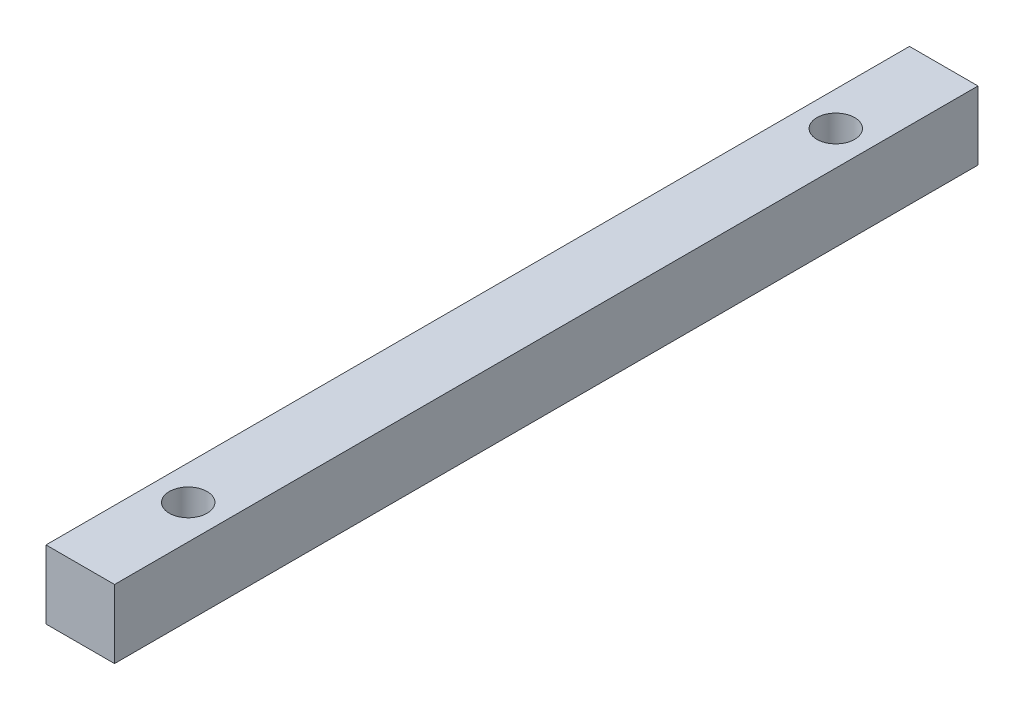
SolidWorks part; units mm, degrees
ref_plane "Front Plane" through (0, 0, 0) normal (0, 0, 1) x (1, 0, 0)
ref_plane "Top Plane" through (0, 0, 0) normal (0, 1, 0) x (1, 0, 0)
ref_plane "Right Plane" through (0, 0, 0) normal (1, 0, 0) x (0, 0, -1)
sketch "Sketch1" plane through (0, 0, 0) normal (0, 0, 1) x (1, 0, 0)
  line L0 (-3.175, 3.175) -> (-3.175, -3.175) construction
  line L1 (-3.175, 3.175) -> (3.175, 3.175) construction
  line L2 (-3.175, 0) -> (0, 0) construction
  line L3 (0, 0) -> (0, 3.175) construction
  dimension "Thickness" = 6.35
  dimension "Width" = 6.35
ref_plane "Plane1" through (-3.175, 3.175, 0) normal (0, -1, 0) x (-1, 0, 0)
sketch "Sketch2" plane through (-3.175, 3.175, 0) normal (0, 1, 0) x (1, 0, 0)
  line L0 (3.175, -609.6) -> (3.175, 609.6) construction
  point P2 (3.175, -596.9)
  point P3 (3.175, 596.9)
  dimension "Length" = 1219.2
  dimension "D1" = 12.7
  dimension "D2" = 12.7
sketch "Sketch3" plane through (0, 0, 0) normal (0, 0, 1) x (1, 0, 0)
  line L1 (-3.175, -3.175) -> (3.175, -3.175)
  line L2 (-3.175, -3.175) -> (-3.175, 3.175)
  line L3 (-3.175, 3.175) -> (3.175, 3.175)
  line L4 (3.175, -3.175) -> (3.175, 3.175)
  line L5 (0, 3.175) -> (0, -3.175) construction
  line L6 (-3.175, 0) -> (3.175, 0) construction
  line L7 (-3.175, 0) -> (0, 0) construction
extrude "Boss-Extrude1" add sketch "Sketch3" along normal up to vertex (609.6 mm away) and the other way up to vertex (609.6 mm away) up to point (0, 3.175, 609.6) other way up to point (0, 3.175, -609.6)
ref_plane "Plane2" through (0, 0, -529.6) normal (0, 0, -1) x (-1, 0, 0)
sketch "Sketch4" plane through (0, 0, -529.6) normal (0, 0, -1) x (-1, 0, 0)
  line L0 (-3.175, -3.175) -> (-3.175, 3.175) construction
  line L1 (-3.675, 3.675) -> (3.675, 3.675)
  line L2 (-3.675, 3.675) -> (-3.675, -3.675)
  line L3 (-3.675, -3.675) -> (3.675, -3.675)
  line L4 (3.675, 3.675) -> (3.675, -3.675)
  line L5 (-3.675, 3.675) -> (3.675, -3.675) construction
  line L6 (-3.675, -3.675) -> (3.675, 3.675) construction
  point P0 (0, 0)
  dimension "D1" = 0.5
extrude "Cut-Extrude1" cut sketch "Sketch4" against normal through all
sketch "Sketch5" plane through (0, 3.175, 0) normal (0, 1, 0) x (1, 0, 0)
  line L0 (3.175, 609.6) -> (-3.175, 609.6) construction
  line L1 (-3.175, 529.6) -> (3.175, 529.6) construction
  line L2 (3.175, 529.6) -> (3.175, 609.6) construction
  circle A0 centre (0, 599.6) radius 1.75
  circle A1 centre (0, 539.6) radius 1.75
  dimension "D2" = 3.5
  dimension "D1" = 10
  dimension "D3" = 10
  dimension "D4" = 3.175
extrude "Cut-Extrude2" cut sketch "Sketch5" against normal through all
equation "\"D1@Sketch2\"=\"Width@Sketch1\"*2"
equation "\"D2@Sketch2\"=\"D1@Sketch2\""
